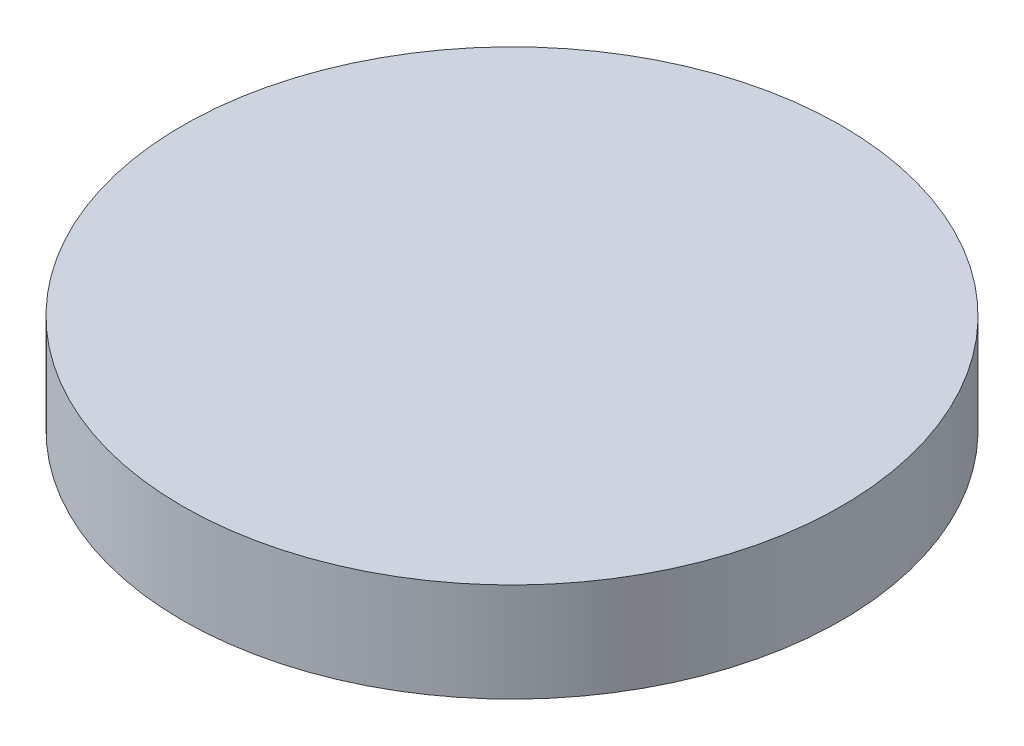
SolidWorks part; units mm, degrees
material "Cast Alloy Steel"
ref_plane "Front Plane" through (0, 0, 0) normal (0, 0, 1) x (1, 0, 0)
ref_plane "Top Plane" through (0, 0, 0) normal (0, 1, 0) x (1, 0, 0)
ref_plane "Right Plane" through (0, 0, 0) normal (1, 0, 0) x (0, 0, -1)
sketch "Sketch1" plane through (0, 0, 0) normal (0, 1, 0) x (1, 0, 0)
  circle A0 centre (0, 0) radius 10
  dimension "D1" = 20
extrude "Boss-Extrude1" add sketch "Sketch1" along normal blind 3
